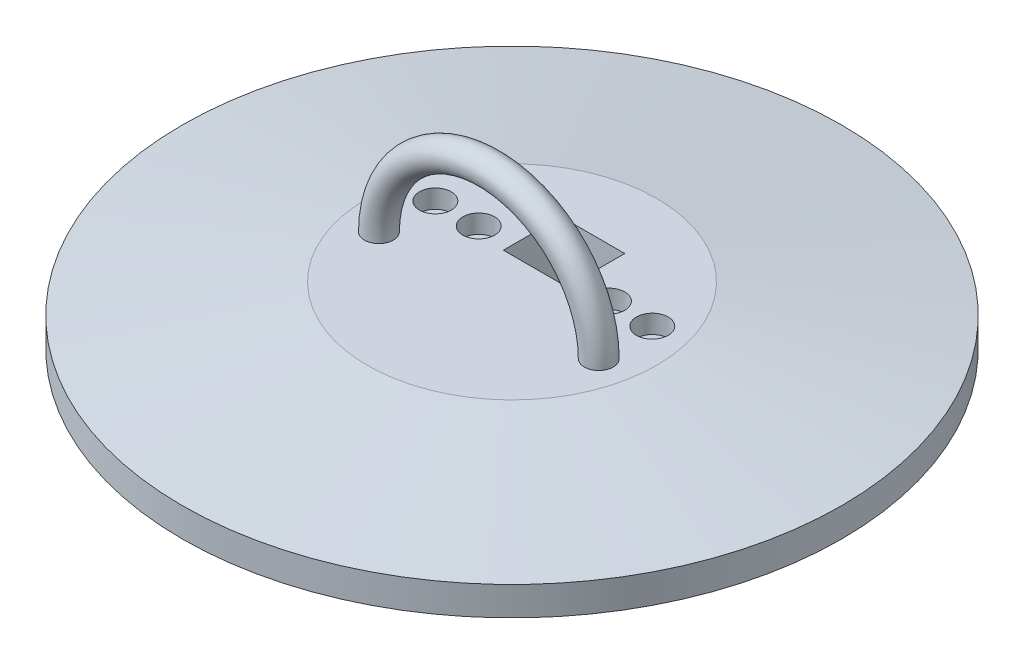
SolidWorks part; units mm, degrees
ref_plane "前基準面" through (0, 0, 0) normal (0, 0, 1) x (1, 0, 0)
ref_plane "上基準面" through (0, 0, 0) normal (0, 1, 0) x (1, 0, 0)
ref_plane "右基準面" through (0, 0, 0) normal (1, 0, 0) x (0, 0, -1)
sketch "草圖1" plane through (0, 0, 0) normal (1, 0, 0) x (0, 0, -1)
  line L0 (0, 0) -> (0, 20)
  line L1 (0, 20) -> (50, 20)
  line L2 (0, 0) -> (114, 0)
  line L3 (114, 0) -> (114, 10)
  line L4 (50, 20) -> (114, 10)
  dimension "D3" = 50
  dimension "D1" = 10
  dimension "D2" = 20
  dimension "D4" = 114
revolve "旋轉1" add sketch "草圖1" angle 360 about L0
sketch "草圖5" plane through (0, 20, 0) normal (0, 1, 0) x (1, 0, 0)
  circle A0 centre (0, 0) radius 50
extrude "填料-伸長1" add sketch "草圖5" against normal blind 35
sketch "草圖2" plane through (0, 20, 0) normal (0, 1, 0) x (1, 0, 0)
  line L1 (11, 8) -> (-11, 8)
  line L2 (11, 8) -> (11, 28)
  line L3 (11, 28) -> (-11, 28)
  line L4 (-11, 8) -> (-11, 28)
  line L5 (11, 8) -> (-11, 28) construction
  line L6 (11, 28) -> (-11, 8) construction
  point P0 (0, 18)
  point P5 (0, 0)
  dimension "D1" = 20
  dimension "D2" = 22
  dimension "D3" = 8
extrude "除料-伸長1" cut sketch "草圖2" against normal through all
hole_wizard "M6 六角承窩頭蓋螺釘的柱孔1" positions "草圖3" profile "草圖4" counterbore size "M6" standard "ISO" end condition through all
sketch "草圖3" plane through (0, 20, 0) normal (0, 1, 0) x (1, 0, 0)
  line L0 (-11, 8) -> (11, 8) construction
  line L1 (11, 8) -> (11, 28) construction
  point P0 (37.5, 11)
  point P2 (22.5, 11)
  point P4 (-22.5, 11)
  point P6 (-37.5, 11)
  point P17 (33.776, 9.5248)
  point P18 (0, 0)
  dimension "D1" = 3
  dimension "D2" = 11.5
  dimension "D3" = 15
  dimension "D4" = 45
  dimension "D5" = 15
sketch "草圖4" plane through (37.5, 20, -11) normal (1, 0, 0) x (0, 0, 1)
  line L0 (0, 0) -> (0, 35)
  line L1 (0, 35) -> (3.3, 35)
  line L3 (3.3, 35) -> (3.3, 6.4)
  line L4 (3.3, 6.4) -> (5.5, 6.4)
  line L5 (5.5, 6.4) -> (5.5, 0)
  line L7 (5.5, 0) -> (0, 0)
  line L11 (0, -6.35) -> (0, 107.95) construction
  dimension "貫穿孔直徑" = 6.6
  dimension "貫穿孔深度" = 35
  dimension "柱孔直徑" = 11
  dimension "柱孔深度" = 6.4
sketch "草圖6" plane through (0, -15, 0) normal (0, -1, 0) x (1, 0, 0)
  line L0 (37.5633, -33) -> (-37.5633, -33)
  line L1 (-38.2167, 32.241) -> (-37.5633, 33)
  line L2 (-37.5633, 33) -> (37.5633, 33)
  arc A0 (-37.5633, -33) -> (37.5633, -33) centre (0, 0) ccw
  arc A1 (37.5633, 33) -> (-38.2167, 32.241) centre (0, 0) ccw
  circle M11 centre (0, 0) radius 50
  dimension "D1" = 100
  dimension "D2" = 33
  dimension "D3" = 33
extrude "除料-伸長5" cut sketch "草圖6" against normal up to surface (15 mm away) contours L2 M11 | L0 M11 up to face at (0, 0, -50)
sketch "草圖7" plane through (0, 20, 0) normal (0, 1, 0) x (1, 0, 0)
  circle A0 centre (38, -8) radius 5
  dimension "D1" = 10
  dimension "D2" = 38
  dimension "D3" = 8
ref_plane "平面1" through (0, 0, 8) normal (0, 0, 1) x (1, 0, 0)
sketch "草圖8" plane through (0, 0, 8) normal (0, 0, 1) x (1, 0, 0)
  line L0 (50, 20) -> (-50, 20) construction
  arc A0 (37.7924, 20) -> (-37.7924, 20) centre (0, 20) ccw
  dimension "D1" = 37.7924
sweep "掃出1" add profiles "草圖7" path "草圖8"
